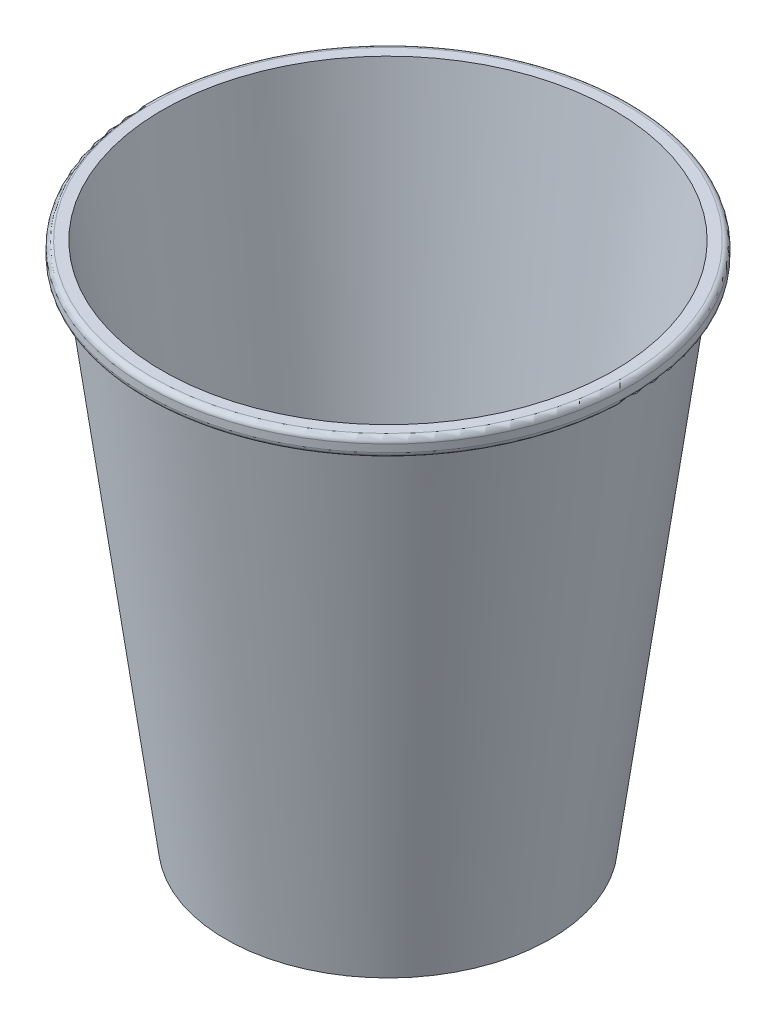
SolidWorks part; units mm, degrees
ref_plane "Alzado" through (0, 0, 0) normal (0, 0, 1) x (1, 0, 0)
ref_plane "Planta" through (0, 0, 0) normal (0, 1, 0) x (1, 0, 0)
ref_plane "Vista lateral" through (0, 0, 0) normal (1, 0, 0) x (0, 0, -1)
sketch "Croquis1" plane through (0, 0, 0) normal (0, 0, 1) x (1, 0, 0)
  line L0 (30.2086, 0) -> (42.5622, 94.1)
  line L1 (30.2086, 0) -> (29.2, 0)
  line L2 (29.2, 0) -> (30.0533, 6.5)
  line L3 (0, 0) -> (0, 7.5) construction
  line L4 (30.0533, 6.5) -> (0, 6.5)
  line L5 (0, 7.5) -> (30.1846, 7.5)
  line L6 (30.1846, 7.5) -> (42, 97.5)
  line L7 (42, 97.5) -> (45, 97.5)
  line L8 (42.5622, 94.1) -> (45, 94.1)
  line L9 (45, 94.1) -> (45, 97.5)
  line L10 (0, 7.5) -> (0, 6.5)
  line L11 (0, 7.5) -> (0, 70) construction
  line L12 (0, 70) -> (39.3983, 70) construction
  dimension "D4" = 42
  dimension "D1" = 29.2
  dimension "D2" = 1
  dimension "D3" = 6.5
  dimension "D5" = 45
  dimension "D6" = 3.4
  dimension "D7" = 90
  dimension "D8" = 1
  dimension "D9" = 70
  dimension "D10" = 39.3983
revolve "Revolución1" add sketch "Croquis1" angle 360 about L3
fillet "Redondeo1" radius 1 2 edges at (0, 94.1, -45) (0, 97.5, -45)
